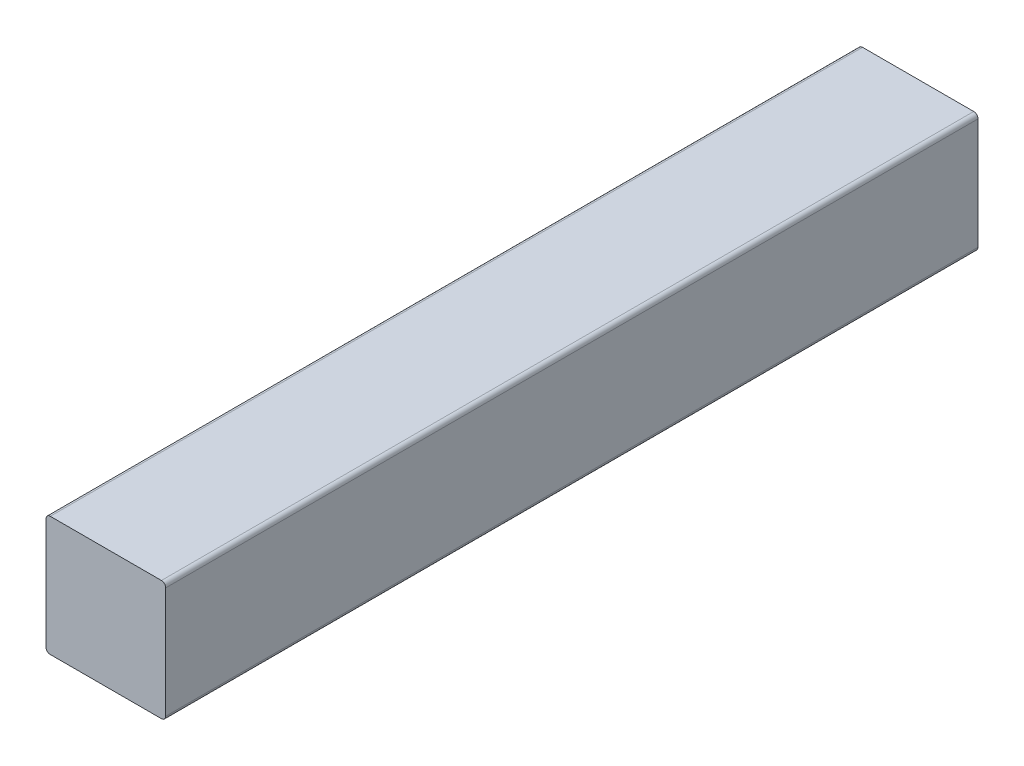
SolidWorks part; units mm, degrees
material "Pine"
ref_plane "Front Plane" through (0, 0, 0) normal (0, 0, 1) x (1, 0, 0)
ref_plane "Top Plane" through (0, 0, 0) normal (0, 1, 0) x (1, 0, 0)
ref_plane "Right Plane" through (0, 0, 0) normal (1, 0, 0) x (0, 0, -1)
sketch "Sketch1" plane through (0, 0, 0) normal (0, 1, 0) x (1, 0, 0)
  line L1 (-44.45, 301.625) -> (44.45, 301.625)
  line L2 (-44.45, 301.625) -> (-44.45, -301.625)
  line L3 (-44.45, -301.625) -> (44.45, -301.625)
  line L4 (44.45, 301.625) -> (44.45, -301.625)
  line L5 (0, -301.625) -> (0, 301.625) construction
  line L6 (-44.45, 0) -> (44.45, 0) construction
  point P0 (0, 0)
  dimension "D1" = 88.9
  dimension "D2" = 603.25
extrude "Boss-Extrude1" add sketch "Sketch1" along normal blind 88.9
fillet "Fillet1" radius 3.175 4 edges at (-44.45, 0, 0) (-44.45, 88.9, 0) (44.45, 0, 0) (44.45, 88.9, 0)
